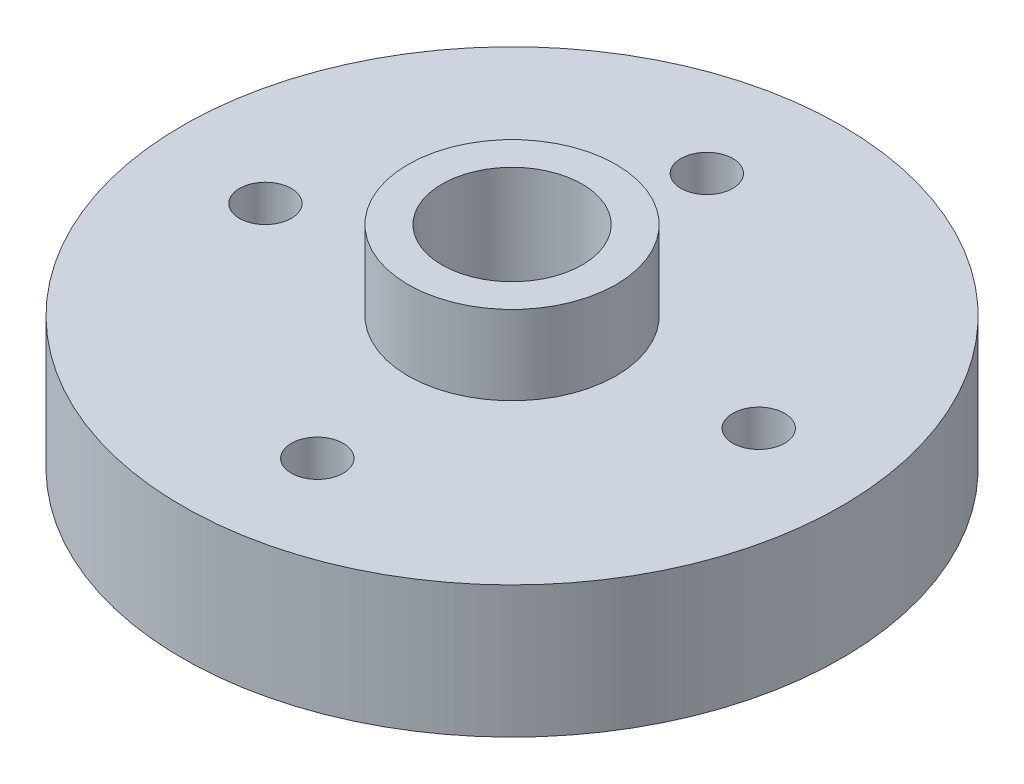
SolidWorks part; units mm, degrees
ref_plane "Front Plane" through (0, 0, 0) normal (0, 0, 1) x (1, 0, 0)
ref_plane "Top Plane" through (0, 0, 0) normal (0, 1, 0) x (1, 0, 0)
ref_plane "Right Plane" through (0, 0, 0) normal (1, 0, 0) x (0, 0, -1)
sketch "Sketch1" plane through (0, 0, 0) normal (0, 1, 0) x (1, 0, 0)
  circle A0 centre (0, 0) radius 9.525
  dimension "D1" = 19.05
extrude "Boss-Extrude1" add sketch "Sketch1" along normal blind 3.81
sketch "Sketch2" plane through (0, 3.81, 0) normal (0, 1, 0) x (1, 0, 0)
  circle A0 centre (0, 0) radius 3.007
extrude "Boss-Extrude2" add sketch "Sketch2" along normal blind 2.286
sketch "Sketch3" plane through (0, 3.81, 0) normal (0, 1, 0) x (1, 0, 0)
  circle A0 centre (-0.75, 6.3788) radius 0.75
  circle A1 centre (6.3788, 0.75) radius 0.75
  circle A2 centre (0.75, -6.3788) radius 0.75
  circle A3 centre (-6.3788, -0.75) radius 0.75
  point P11 (0, 0)
  dimension "D1" = 4
extrude "Cut-Extrude1" cut sketch "Sketch3" against normal blind 12.446
sketch "Sketch4" plane through (0, 6.096, 0) normal (0, 1, 0) x (1, 0, 0)
  circle A0 centre (0, 0) radius 2.0265
extrude "Cut-Extrude2" cut sketch "Sketch4" against normal blind 12.446
